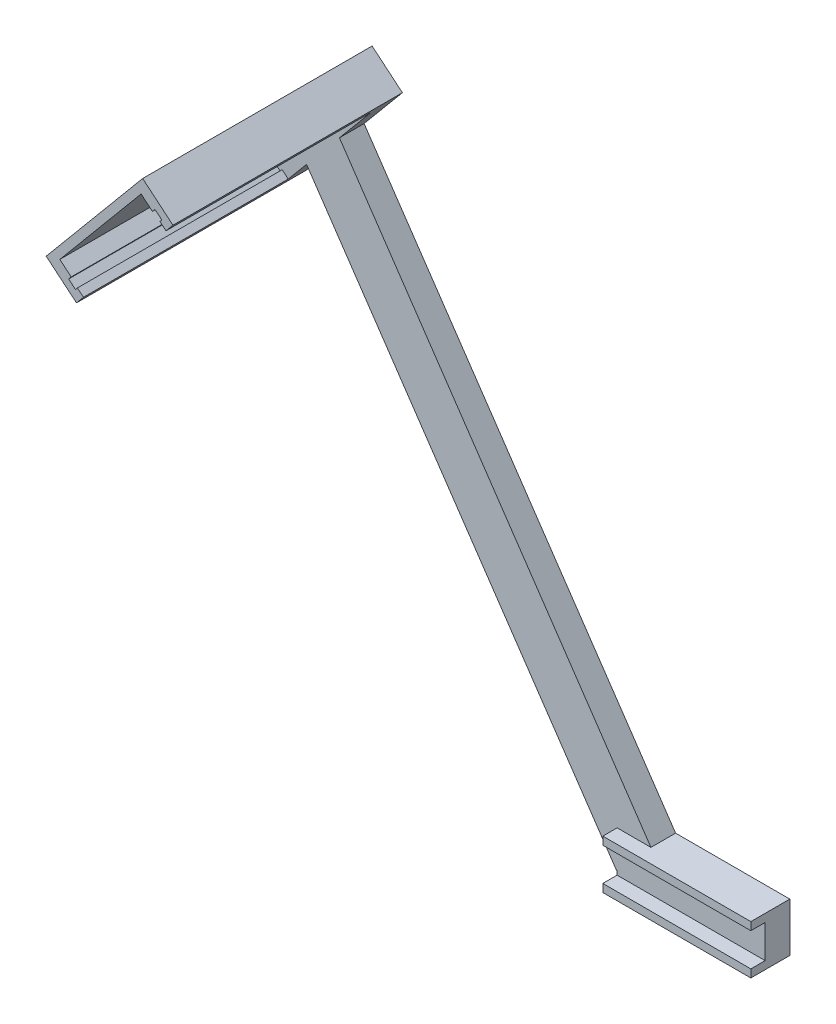
SolidWorks part; units mm, degrees
ref_plane "Front Plane" through (0, 0, 0) normal (0, 0, 1) x (1, 0, 0)
ref_plane "Top Plane" through (0, 0, 0) normal (0, 1, 0) x (1, 0, 0)
ref_plane "Right Plane" through (0, 0, 0) normal (1, 0, 0) x (0, 0, -1)
ref_plane "Plano_cara_cama" through (0, 0, -133.1) normal (0, 0, 1) x (1, 0, 0)
ref_plane "Plano_cara_labio" through (0, 0, -128.1) normal (0, 0, 1) x (1, 0, 0)
sketch "Croquis_placa_clip" plane through (0, 0, -133.1) normal (0, 0, 1) x (1, 0, 0)
  line L1 (-54, 74.8) -> (-24, 74.8)
  line L2 (-54, 74.8) -> (-54, 84.7)
  line L3 (-54, 84.7) -> (-24, 84.7)
  line L4 (-24, 74.8) -> (-24, 84.7)
  line L5 (-54, 74.8) -> (-24, 84.7) construction
  line L6 (-54, 84.7) -> (-24, 74.8) construction
  point P5 (0, 0)
  dimension "D1" = 30
  dimension "D2" = 9.9
  dimension "D3" = 54
  dimension "D4" = 84.7
extrude "Placa_clip" add sketch "Croquis_placa_clip" along normal blind 5
sketch "Croquis_mordazas" plane through (0, 0, -128.1) normal (0, 0, 1) x (1, 0, 0)
  line L1 (-54, 83.1) -> (-24, 83.1)
  line L2 (-54, 83.1) -> (-54, 84.7)
  line L3 (-54, 84.7) -> (-24, 84.7)
  line L4 (-24, 83.1) -> (-24, 84.7)
  line L5 (-54, 83.1) -> (-24, 84.7) construction
  line L6 (-54, 84.7) -> (-24, 83.1) construction
  line L7 (-54, 74.8) -> (-24, 74.8)
  line L8 (-54, 74.8) -> (-54, 76.4)
  line L9 (-54, 76.4) -> (-24, 76.4)
  line L10 (-24, 74.8) -> (-24, 76.4)
  line L11 (-54, 74.8) -> (-24, 76.4) construction
  line L12 (-54, 76.4) -> (-24, 74.8) construction
  point P0 (-39, 83.9)
  point P6 (-39, 75.6)
  point P13 (0, 0)
  dimension "D1" = 30
  dimension "D2" = 1.6
  dimension "D3" = 30
  dimension "D4" = 1.6
  dimension "D5" = 54
  dimension "D6" = 8.3
  dimension "D7" = 84.7
extrude "Mordazas" add sketch "Croquis_mordazas" along normal blind 2.9
sketch "Croquis_brazo" plane through (0, 0, -133.1) normal (0, 0, 1) x (1, 0, 0)
  line L0 (-54.1366, 77.1914) -> (-121.9447, 177.0612)
  line L1 (-121.9447, 177.0612) -> (-113.6715, 182.6784)
  line L2 (-113.6715, 182.6784) -> (-45.8634, 82.8086)
  line L3 (-45.8634, 82.8086) -> (-54.1366, 77.1914)
extrude "Brazo" add sketch "Croquis_brazo" along normal blind 5
sketch "Croquis_tope" plane through (0, 0, -133.1) normal (0, 0, 1) x (1, 0, 0)
  line L0 (-128.1965, 168.6768) -> (-108.6479, 192.0883)
  line L1 (-108.6479, 192.0883) -> (-102.5071, 186.9608)
  line L2 (-102.5071, 186.9608) -> (-122.0558, 163.5493)
  line L3 (-122.0558, 163.5493) -> (-128.1965, 168.6768)
extrude "Tope_cuna" add sketch "Croquis_tope" along normal blind 5
sketch "Croquis_cuna" plane through (0, 0, -133.1) normal (0, 0, 1) x (1, 0, 0)
  line L0 (-108.6479, 192.0883) -> (-102.5071, 186.9608)
  line L1 (-102.5071, 186.9608) -> (-103.9172, 185.2721)
  line L2 (-103.9172, 185.2721) -> (-105.1454, 186.2976)
  line L3 (-105.1454, 186.2976) -> (-104.7608, 186.7582)
  line L4 (-104.7608, 186.7582) -> (-106.1425, 187.9118)
  line L5 (-106.1425, 187.9118) -> (-106.6552, 187.2978)
  line L6 (-106.6552, 187.2978) -> (-108.958, 189.2206)
  line L7 (-108.958, 189.2206) -> (-125.4301, 169.4935)
  line L8 (-125.4301, 169.4935) -> (-123.1273, 167.5707)
  line L9 (-123.1273, 167.5707) -> (-123.6401, 166.9566)
  line L10 (-123.6401, 166.9566) -> (-122.2584, 165.8029)
  line L11 (-122.2584, 165.8029) -> (-121.8739, 166.2635)
  line L12 (-121.8739, 166.2635) -> (-120.6457, 165.238)
  line L13 (-120.6457, 165.238) -> (-122.0558, 163.5493)
  line L14 (-122.0558, 163.5493) -> (-128.1965, 168.6768)
  line L15 (-128.1965, 168.6768) -> (-108.6479, 192.0883)
extrude "Cuna" add sketch "Croquis_cuna" along normal blind 46.5
